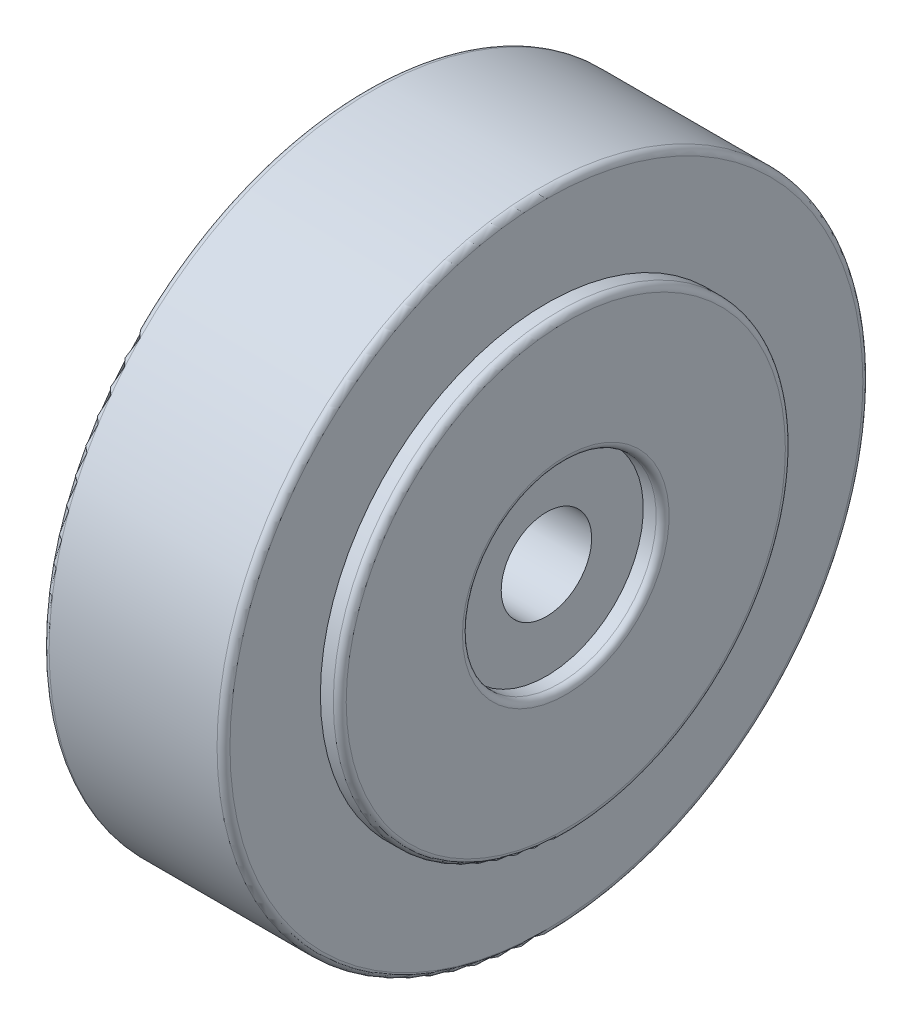
SolidWorks part; units mm, degrees
ref_plane "Front Plane" through (0, 0, 0) normal (0, 0, 1) x (1, 0, 0)
ref_plane "Top Plane" through (0, 0, 0) normal (0, 1, 0) x (1, 0, 0)
ref_plane "Right Plane" through (0, 0, 0) normal (1, 0, 0) x (0, 0, -1)
sketch "Sketch1" plane through (0, 0, 0) normal (0, 0, 1) x (1, 0, 0)
  line L0 (0, 0) -> (0, 64.5551) construction
  line L1 (0, 0) -> (69.5484, 0) construction
  line L2 (14, 7) -> (14, 15)
  line L3 (14, 15) -> (17, 15)
  line L4 (17, 15) -> (17, 35)
  line L5 (17, 35) -> (14, 35)
  line L6 (14, 35) -> (14, 50)
  line L7 (-14, 35) -> (-14, 50)
  line L8 (-17, 35) -> (-14, 35)
  line L9 (-17, 15) -> (-17, 35)
  line L10 (-14, 15) -> (-17, 15)
  line L11 (-14, 7) -> (-14, 15)
  line L12 (-14, 50) -> (14, 50)
  line L13 (-14, 7) -> (14, 7)
  dimension "D1" = 14
  dimension "D2" = 30
  dimension "D3" = 70
  dimension "D4" = 100
  dimension "D5" = 28
  dimension "D6" = 3
revolve "Revolve1" add sketch "Sketch1" angle 360 about L1
fillet "Fillet1" radius 1 6 edges at (17, 0, 35) (14, 0, 50) (-17, 0, 35) (-17, 0, 15) (-14, 0, 50) (17, 0, 15)
